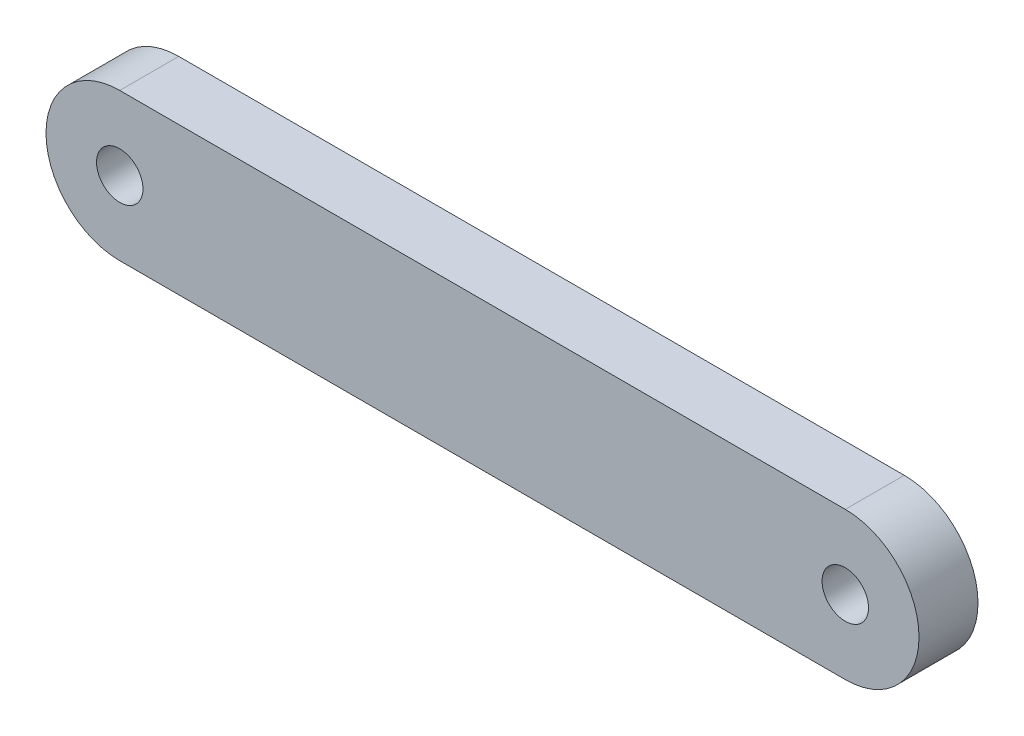
SolidWorks part; units mm, degrees
ref_plane "Front Plane" through (0, 0, 0) normal (0, 0, 1) x (1, 0, 0)
ref_plane "Top Plane" through (0, 0, 0) normal (0, 1, 0) x (1, 0, 0)
ref_plane "Right Plane" through (0, 0, 0) normal (1, 0, 0) x (0, 0, -1)
sketch "Sketch1" plane through (0, 0, 0) normal (0, 0, 1) x (1, 0, 0)
  line L0 (0, 0) -> (62.484, 0) construction
  line L1 (0, 6.35) -> (62.484, 6.35)
  line L2 (0, -6.35) -> (62.484, -6.35)
  arc A0 (0, 6.35) -> (0, -6.35) centre (0, 0) ccw
  arc A1 (62.484, -6.35) -> (62.484, 6.35) centre (62.484, 0) ccw
  circle A2 centre (0, 0) radius 2
  circle A3 centre (62.484, 0) radius 2
  point P3 (31.242, 0)
  dimension "D3" = 4
  dimension "D1" = 6.35
  dimension "D2" = 62.484
extrude "Boss-Extrude1" add sketch "Sketch1" along normal blind 5.08
